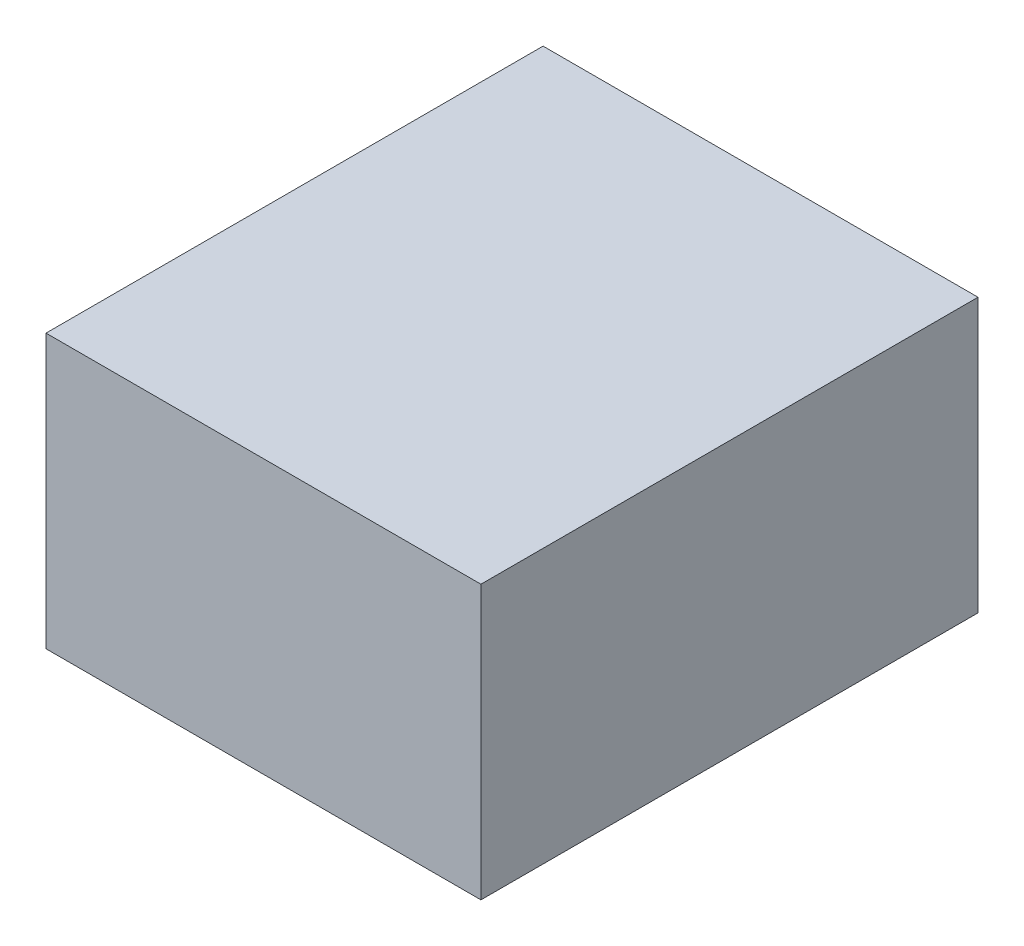
SolidWorks part; units mm, degrees
ref_plane "Piano frontale" through (0, 0, 0) normal (0, 0, 1) x (1, 0, 0)
ref_plane "Piano superiore" through (0, 0, 0) normal (0, 1, 0) x (1, 0, 0)
ref_plane "Piano destro" through (0, 0, 0) normal (1, 0, 0) x (0, 0, -1)
sketch "Schizzo1" plane through (0, 0, 0) normal (0, 1, 0) x (1, 0, 0)
  line L1 (-2.7078, -7.4773) -> (-0.9578, -7.4773)
  line L2 (-2.7078, -7.4773) -> (-2.7078, -9.4773)
  line L3 (-2.7078, -9.4773) -> (-0.9578, -9.4773)
  line L4 (-0.9578, -7.4773) -> (-0.9578, -9.4773)
  dimension "D1" = 2
  dimension "D2" = 1.75
extrude "Estrusione-Estrusione1" add sketch "Schizzo1" along normal blind 1.1
